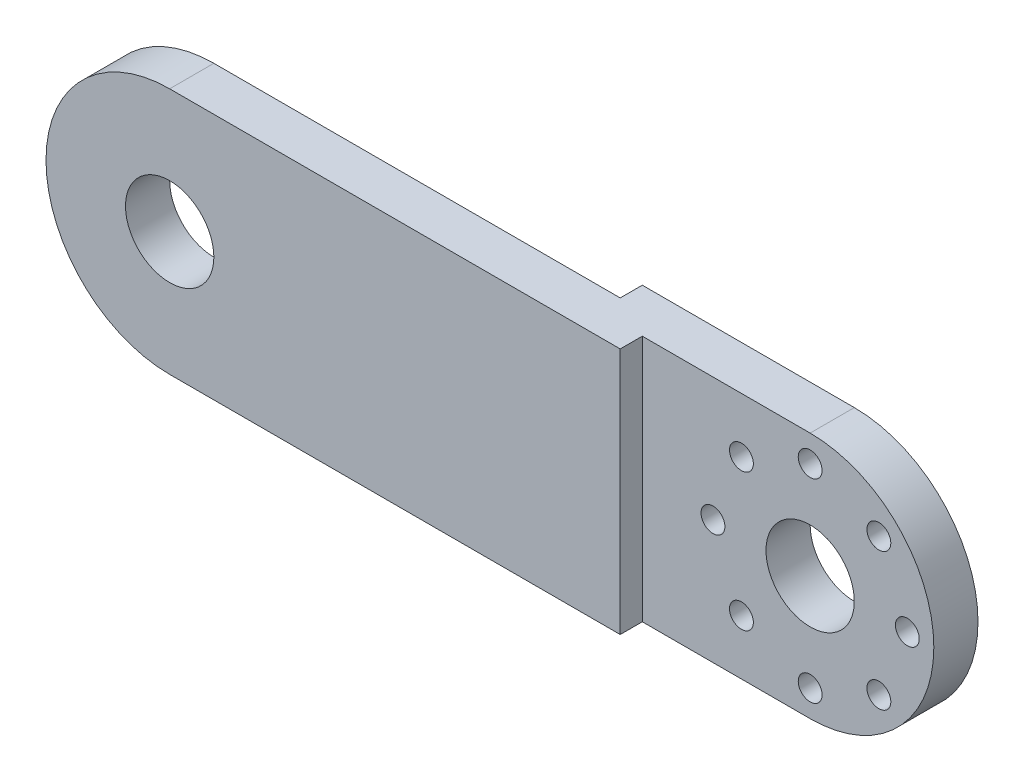
SolidWorks part; units mm, degrees
ref_plane "Plano frontal" through (0, 0, 0) normal (0, 0, 1) x (1, 0, 0)
ref_plane "Plano superior" through (0, 0, 0) normal (0, 1, 0) x (1, 0, 0)
ref_plane "Plano direito" through (0, 0, 0) normal (1, 0, 0) x (0, 0, -1)
sketch "Esboço1" plane through (0, 0, 0) normal (0, 0, 1) x (1, 0, 0)
  line L0 (0, -14) -> (122, -14)
  line L1 (0, 14) -> (122, 14)
  arc A0 (0, 14) -> (0, -14) centre (0, 0) ccw
  arc A1 (122, -14) -> (122, 14) centre (122, 0) ccw
  dimension "D1" = 28
  dimension "D2" = 28
  dimension "D3" = 122
extrude "Ressalto-extrusão1" add sketch "Esboço1" along normal blind 5
sketch "Esboço2" plane through (0, 0, 0) normal (0, 0, -1) x (-1, 0, 0)
  circle A1 centre (-125.3271, 10.4848) radius 1.35
  circle A2 centre (-116.9388, 9.7665) radius 1.35
  circle A3 centre (-111.5152, 3.3271) radius 1.35
  circle A4 centre (-112.2335, -5.0612) radius 1.35
  circle A5 centre (-118.6729, -10.4848) radius 1.3731
  circle A6 centre (-127.0612, -9.7665) radius 1.3301
  circle A7 centre (-132.4848, -3.3271) radius 1.35
  circle A8 centre (-131.7665, 5.0612) radius 1.35
  circle A9 centre (-122, 0) radius 5
extrude "Corte-extrusão1" cut sketch "Esboço2" against normal through all
sketch "Esboço3" plane through (0, 0, 0) normal (0, 0, -1) x (-1, 0, 0)
  circle A0 centre (0, 0) radius 5
extrude "Corte-extrusão2" cut sketch "Esboço3" against normal through all
sketch "Esboço5" plane through (0, 0, 0) normal (0, 0, -1) x (-1, 0, 0)
  line L0 (-106, 14) -> (-137.2412, 14)
  line L1 (-106, 14) -> (-106, -14)
  line L2 (-122, 14) -> (0, 14) construction
  line L3 (0, -14) -> (-122, -14) construction
  line L4 (-137.2412, 14) -> (-137.2412, -14)
  line L5 (-137.2412, -14) -> (-106, -14)
extrude "Corte-extrusão3" cut sketch "Esboço5" against normal through all
sketch "Esboço6" plane through (0, 0, 0) normal (0, 0, -1) x (-1, 0, 0)
  line L0 (-106, 14) -> (-101, 14)
  line L1 (-106, 14) -> (0, 14) construction
  line L2 (-101, 14) -> (-101, -14)
  line L3 (0, -14) -> (-106, -14) construction
  line L4 (-101, -14) -> (-106, -14)
  line L5 (-106, -14) -> (-106, 14)
extrude "Ressalto-extrusão2" add sketch "Esboço6" along normal blind 2.5
sketch "Esboço7" plane through (0, 0, -2.5) normal (0, 0, -1) x (-1, 0, 0)
  line L0 (-106, 14) -> (-120, 14)
  line L1 (-106, 14) -> (-106, -14) construction
  line L2 (-106, -14) -> (-120, -14)
  line L8 (-106, 14) -> (-106, -14)
  line L9 (-106, -14) -> (-101, -14)
  line L10 (-101, -14) -> (-101, 14)
  line L11 (-101, 14) -> (-106, 14)
  line L12 (-106, 14) -> (-106, -14)
  arc A0 (-120, 14) -> (-120, -14) centre (-120, 0) ccw
  dimension "D1" = 14
  dimension "D2" = 14
  dimension "D3" = 0
extrude "Ressalto-extrusão4" add sketch "Esboço7" against normal blind 5
sketch "Esboço8" plane through (0, 0, -2.5) normal (0, 0, -1) x (-1, 0, 0)
  circle A1 centre (-120, 0) radius 5
  circle A2 centre (-120, 11) radius 1.35
  circle A3 centre (-109, 0) radius 1.35
  circle A4 centre (-120, -11) radius 1.35
  circle A5 centre (-131, 0) radius 1.35
  circle A6 centre (-112.2218, 7.7782) radius 1.35
  circle A7 centre (-112.2218, -7.7782) radius 1.35
  circle A8 centre (-127.7782, -7.7782) radius 1.35
  circle A9 centre (-127.7782, 7.7782) radius 1.35
  dimension "D1" = 2.7
  dimension "D2" = 2.7
  dimension "D3" = 11
  dimension "D4" = 11
  dimension "D5" = 11
  dimension "D6" = 11
extrude "Corte-extrusão4" cut sketch "Esboço8" against normal through all
sketch "Esboço10" plane through (0, -14, 0) normal (0, -1, 0) x (1, 0, 0)
  line L0 (106, 2.5) -> (101, 2.5)
  line L1 (101, 2.5) -> (101, 5)
  line L2 (0, 5) -> (106, 5) construction
  line L3 (101, 5) -> (106, 5)
  line L4 (106, 5) -> (106, 2.5)
  line L5 (101, 0) -> (96, 0)
  line L6 (0, 0) -> (101, 0) construction
  line L7 (101, 0) -> (101, -2.5)
  line L8 (101, -2.5) -> (96, -2.5)
  line L9 (96, -2.5) -> (96, 0)
extrude "Corte-extrusão5" cut sketch "Esboço10" against normal through all contours L1 L3 L4 L0
sketch "Esboço11" plane through (0, -14, 0) normal (0, -1, 0) x (1, 0, 0)
  line L4 (101, 0) -> (96, 0)
  line L5 (0, 0) -> (101, 0) construction
  line L6 (101, 0) -> (101, -2.5)
  line L7 (101, -2.5) -> (96, -2.5)
  line L8 (96, -2.5) -> (96, 0)
extrude "Ressalto-extrusão5" add sketch "Esboço11" against normal through all
sketch "Esboço14" plane through (0, 0, 0) normal (0, 0, -1) x (-1, 0, 0)
  line L0 (-36, 14) -> (15.5458, 14)
  line L1 (-36, -14) -> (-36, 14)
  line L2 (0, -14) -> (-96, -14) construction
  line L3 (-96, 14) -> (0, 14) construction
  line L4 (15.5458, 14) -> (15.5458, -14)
  line L5 (15.5458, -14) -> (-36, -14)
extrude "Corte-extrusão6" cut sketch "Esboço14" against normal blind 10
sketch "Esboço15" plane through (0, 0, 0) normal (0, 0, -1) x (-1, 0, 0)
  line L0 (-36, 0) -> (-50, 0)
  line L1 (-36, 14) -> (-36, -14) construction
  line L2 (-96, 14) -> (-36, 14) construction
  line L3 (-50, 14) -> (-36, 14)
  line L4 (-36, 14) -> (-36, -14)
  line L5 (-36, -14) -> (-50, -14)
  arc A0 (-50, 14) -> (-50, -14) centre (-50, 0) cw
  line M2 (-96, -14) -> (-36, -14)
  line M3 (-36, -14) -> (-36, 14)
  line M4 (-36, 14) -> (-96, 14)
  dimension "D1" = 14
extrude "Corte-extrusão7" cut sketch "Esboço15" against normal blind 10 and the other way through all contours A0 M4 M3 | A0 M3 M2
sketch "Esboço16" plane through (0, 0, 0) normal (0, 0, -1) x (-1, 0, 0)
  line L0 (-36, 0) -> (-50, 0)
  arc A0 (-50, -14) -> (-50, 14) centre (-50, 0) ccw construction
  circle A1 centre (-50, 0) radius 5
extrude "Corte-extrusão8" cut sketch "Esboço16" against normal blind 10
